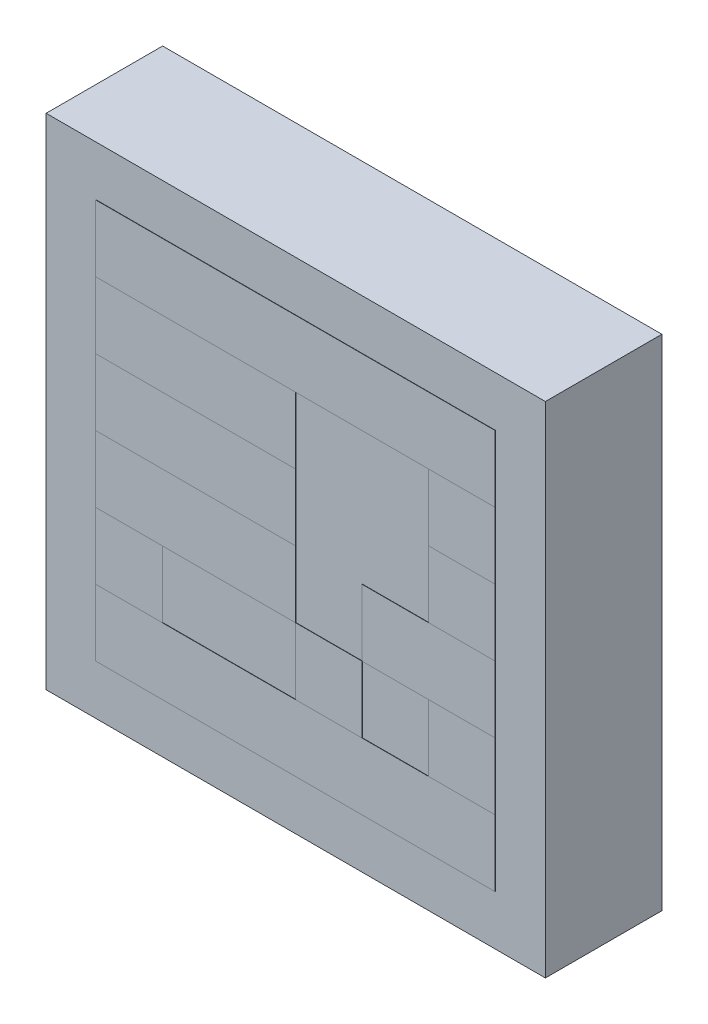
SolidWorks part; units mm, degrees
ref_plane "前视基准面" through (0, 0, 0) normal (0, 0, 1) x (1, 0, 0)
ref_plane "上视基准面" through (0, 0, 0) normal (0, 1, 0) x (1, 0, 0)
ref_plane "右视基准面" through (0, 0, 0) normal (1, 0, 0) x (0, 0, -1)
other "Configuration Table"
sketch "草图1" plane through (0, 0, 0) normal (0, 0, 1) x (1, 0, 0)
  line L1 (-30, -30) -> (30, -30)
  line L2 (-30, -30) -> (-30, 30)
  line L3 (-30, 30) -> (30, 30)
  line L4 (30, -30) -> (30, 30)
  dimension "D1" = 30
  dimension "D2" = 30
  dimension "D3" = 30
extrude "Coplanar_support60x60x14" add sketch "草图1" against normal blind 14
sketch "草图2" plane through (0, 0, 0) normal (0, 0, 1) x (1, 0, 0)
  line L1 (-24, 16) -> (24, 16)
  line L2 (-24, 16) -> (-24, 24)
  line L3 (-24, 24) -> (24, 24)
  line L4 (24, 16) -> (24, 24)
extrude "ID2_row0" add sketch "草图2" along normal blind 0.04 separate body
sketch "草图3" plane through (0, 0, 0) normal (0, 0, 1) x (1, 0, 0)
  line L1 (-24, 8) -> (0, 8)
  line L2 (-24, 8) -> (-24, 16)
  line L3 (-24, 16) -> (0, 16)
  line L4 (0, 8) -> (0, 16)
  line L6 (16, 8) -> (24, 8)
  line L7 (16, 8) -> (16, 16)
  line L8 (16, 16) -> (24, 16)
  line L9 (24, 8) -> (24, 16)
extrude "ID2_row1" add sketch "草图3" along normal blind 0.04 separate body
sketch "草图4" plane through (0, 0, 0) normal (0, 0, 1) x (1, 0, 0)
  line L1 (-24, 0) -> (0, 0)
  line L2 (-24, 0) -> (-24, 8)
  line L3 (-24, 8) -> (0, 8)
  line L4 (0, 0) -> (0, 8)
  line L6 (16, 0) -> (24, 0)
  line L7 (16, 0) -> (16, 8)
  line L8 (16, 8) -> (24, 8)
  line L9 (24, 0) -> (24, 8)
extrude "ID2_row2" add sketch "草图4" along normal blind 0.04 separate body
sketch "草图5" plane through (0, 0, 0) normal (0, 0, 1) x (1, 0, 0)
  line L1 (-24, -8) -> (0, -8)
  line L2 (-24, -8) -> (-24, 0)
  line L3 (-24, 0) -> (0, 0)
  line L4 (0, -8) -> (0, 0)
  line L6 (8, -8) -> (24, -8)
  line L7 (8, -8) -> (8, 0)
  line L8 (8, 0) -> (24, 0)
  line L9 (24, -8) -> (24, 0)
extrude "ID2_row3" add sketch "草图5" along normal blind 0.04 separate body
sketch "草图6" plane through (0, 0, 0) normal (0, 0, 1) x (1, 0, 0)
  line L1 (-24, -16) -> (-16, -16)
  line L2 (-24, -16) -> (-24, -8)
  line L3 (-24, -8) -> (-16, -8)
  line L4 (-16, -16) -> (-16, -8)
  line L6 (0, -16) -> (8, -16)
  line L7 (0, -16) -> (0, -8)
  line L8 (0, -8) -> (8, -8)
  line L9 (8, -16) -> (8, -8)
  line L11 (16, -16) -> (24, -16)
  line L12 (16, -16) -> (16, -8)
  line L13 (16, -8) -> (24, -8)
  line L14 (24, -16) -> (24, -8)
extrude "ID2_row4" add sketch "草图6" along normal blind 0.04 separate body
sketch "草图7" plane through (0, 0, 0) normal (0, 0, 1) x (1, 0, 0)
  line L1 (-24, -24) -> (24, -24)
  line L2 (-24, -24) -> (-24, -16)
  line L3 (-24, -16) -> (24, -16)
  line L4 (24, -24) -> (24, -16)
extrude "ID2_row5" add sketch "草图7" along normal blind 0.04 separate body
